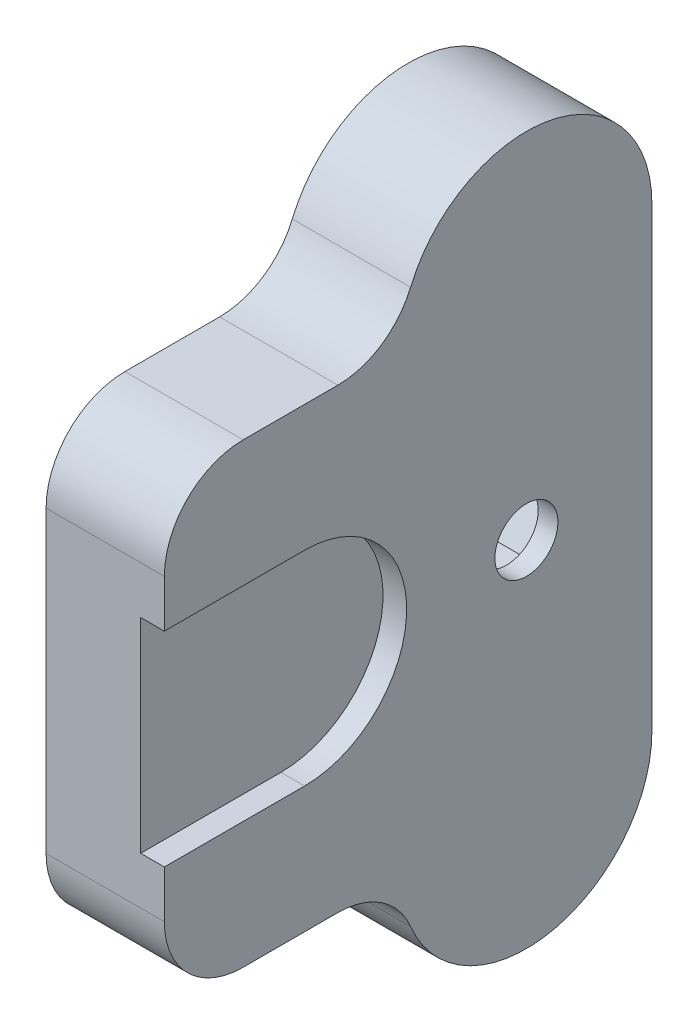
SolidWorks part; units mm, degrees
ref_plane "Front Plane" through (0, 0, 0) normal (1, 0, 0) x (0, 1, 0)
ref_plane "Top Plane" through (0, 0, 0) normal (0, 0, 1) x (0, 1, 0)
ref_plane "Right Plane" through (0, 0, 0) normal (0, 1, 0) x (-1, 0, 0)
sketch "Sketch1" plane through (0, 0, 0) normal (1, 0, 0) x (0, 1, 0)
  line L0 (-28.9545, 0) -> (33.8464, 0) construction
  line L3 (-28.9686, 19.054) -> (-28.9686, -12.7893) construction
  line L4 (0, 49.054) -> (0, -56.7378) construction
  line L6 (-28.9686, -12.7893) -> (28.9686, -12.7893)
  line L7 (44.5791, 0) -> (-44.5791, 0) construction
  line L9 (18.9686, 49.054) -> (-18.9686, 49.054)
  line L12 (-28.9686, 39.054) -> (-28.9686, 27.0474)
  line L13 (28.9686, 19.054) -> (28.9686, -12.7893) construction
  line L14 (28.9686, 39.054) -> (28.9686, 27.0474)
  line L15 (-28.9686, 19.054) -> (28.9686, 19.054) construction
  line L16 (-28.9686, 19.054) -> (28.9686, 19.054) construction
  arc A3 (-35.1108, 17.8215) -> (-28.9686, -12.7893) centre (-28.9686, 3.1323) ccw
  arc A4 (-18.9686, 49.054) -> (-28.9686, 39.054) centre (-18.9686, 39.054) ccw
  arc A5 (-35.1108, 17.8215) -> (-28.9686, 27.0474) centre (-38.9686, 27.0474) ccw
  arc A6 (35.1108, 17.8215) -> (28.9686, 27.0474) centre (38.9686, 27.0474) cw
  arc A7 (18.9686, 49.054) -> (28.9686, 39.054) centre (18.9686, 39.054) cw
  arc A8 (35.1108, 17.8215) -> (28.9686, -12.7893) centre (28.9686, 3.1323) cw
  point P20 (0, 0)
  dimension "D1" = 10
  dimension "D2" = 10
extrude "Boss-Extrude3" add sketch "Sketch1" along normal blind 15
sketch "Sketch3" plane through (15, 0, 0) normal (1, 0, 0) x (0, 1, 0)
  line L0 (-44.8903, 3.1323) -> (44.8903, 3.1323) construction
  line L2 (-28.9686, -12.7893) -> (28.9686, -12.7893) construction
  line L3 (0, -12.7893) -> (0, 49.054) construction
  line L4 (18.9686, 49.054) -> (-18.9686, 49.054) construction
  arc A3 (-35.1108, 17.8215) -> (-28.9686, -12.7893) centre (-28.9686, 3.1323) ccw construction
  arc A4 (28.9686, -12.7893) -> (35.1108, 17.8215) centre (28.9686, 3.1323) ccw construction
  circle A5 centre (0, 3.1323) radius 4
extrude "Cut-Extrude3" cut sketch "Sketch3" against normal blind 14.0462
sketch "Sketch4" plane through (15, 0, 0) normal (1, 0, 0) x (0, 1, 0)
  line L0 (-12.95, 49.054) -> (-12.95, 31.2677)
  line L4 (18.9686, 49.054) -> (-18.9686, 49.054) construction
  line L6 (0, 7.1323) -> (0, 31.2677) construction
  line L7 (12.95, 31.2677) -> (12.95, 49.054)
  line L8 (-12.95, 49.054) -> (12.95, 49.054)
  circle A1 centre (0, 3.1323) radius 4 construction
  circle A2 centre (0, 31.2677) radius 12.95 construction
  arc A3 (-12.95, 31.2677) -> (12.95, 31.2677) centre (0, 31.2677) ccw
extrude "Cut-Extrude4" cut sketch "Sketch4" against normal blind 3
sketch "Sketch5" plane through (15, 0, 0) normal (1, 0, 0) x (0, 1, 0)
  line L0 (-2.9918, 7.8662) -> (2.9918, -1.6015) construction
  line L1 (5.4662, 6.587) -> (-0.2587, 9.5935)
  line L2 (-0.2587, 9.5935) -> (-5.7249, 6.1388)
  line L3 (-5.7249, 6.1388) -> (-5.4662, -0.3223)
  line L4 (-5.4662, -0.3223) -> (0.2587, -3.3288)
  line L5 (0.2587, -3.3288) -> (5.7249, 0.1258)
  line L6 (5.7249, 0.1258) -> (5.4662, 6.587)
  circle A0 centre (0, 3.1323) radius 5.6 construction
  point P11 (0, 0)
  dimension "D1" = 11.2
extrude "Cut-Extrude5" cut sketch "Sketch5" along direction (1, 0, 0) on the side against the normal mid plane 25 from surface at -15 starting at face at (0, 0, 23.7628)
